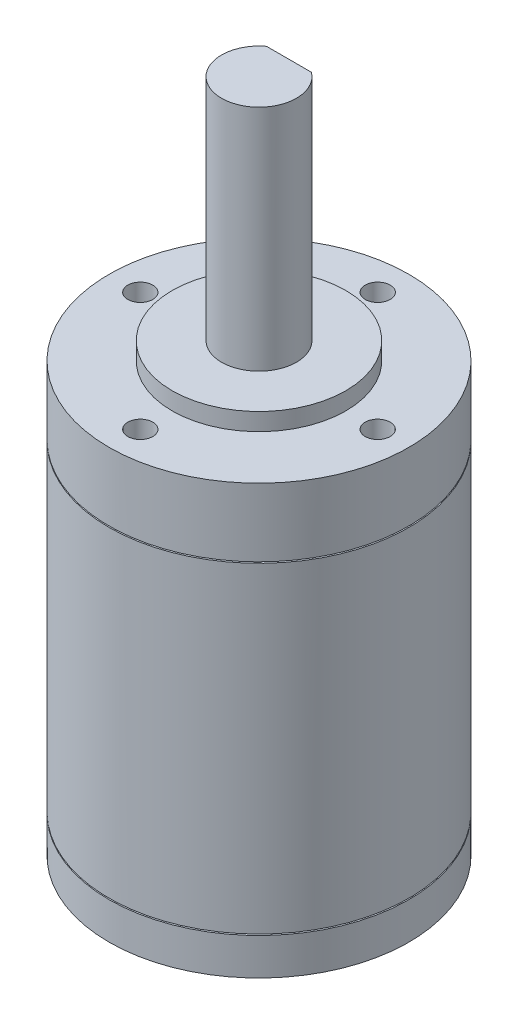
SolidWorks part; units mm, degrees
material "可锻铸铁"
ref_plane "前视" through (0, 0, 0) normal (0, 0, 1) x (1, 0, 0)
ref_plane "上视" through (0, 0, 0) normal (0, 1, 0) x (1, 0, 0)
ref_plane "右视" through (0, 0, 0) normal (1, 0, 0) x (0, 0, -1)
sketch "草图1" plane through (0, 0, 0) normal (0, 1, 0) x (1, 0, 0)
  circle A0 centre (0, 0) radius 12
  dimension "D1" = 24
extrude "凸台-拉伸1" add sketch "草图1" along normal blind 34.3
shell "抽壳6" thickness 2.1
sketch "草图2" plane through (0, 34.3, 0) normal (0, 1, 0) x (1, 0, 0)
  circle A0 centre (0, 0) radius 6.95
  dimension "D1" = 13.9
extrude "凸台-拉伸2" add sketch "草图2" along normal blind 1.4
sketch "草图3" plane through (0, 35.7, 0) normal (0, 1, 0) x (1, 0, 0)
  circle A0 centre (0, 0) radius 3
  dimension "D1" = 6
extrude "凸台-拉伸3" add sketch "草图3" along normal blind 18.3
sketch "草图4" plane through (0, 54, 0) normal (0, 1, 0) x (1, 0, 0)
  line L0 (-4.1804, 2.4) -> (5.155, 2.4)
  line L1 (5.155, 2.4) -> (-0.7181, 5.6828)
  line L2 (-0.7181, 5.6828) -> (-4.1804, 2.4)
  dimension "D1" = 2.4
extrude "切除-拉伸1" cut sketch "草图4" against normal blind 15
sketch "草图5" plane through (0, 0, 0) normal (0, -1, 0) x (1, 0, 0)
  circle A0 centre (0, 0) radius 3.1
  dimension "D1" = 6.2
extrude "切除-拉伸2" cut sketch "草图5" against normal blind 10
chamfer "倒角1" distance 0.9 angle 45 1 edges at (0, 0, -3.1)
sketch "草图7" plane through (0, 34.3, 0) normal (0, 1, 0) x (1, 0, 0)
  circle A0 centre (0, 9.5) radius 1
  dimension "D1" = 2
  dimension "D2" = 9.5
extrude "切除-拉伸3" cut sketch "草图7" against normal blind 10
pattern_circular "阵列(圆周)1" count 4 over 360 about axis through (0, 0, 0) along (0, 1, 0) of "切除-拉伸3"
sketch "草图8" plane through (0, 0, 0) normal (0, -1, 0) x (1, 0, 0)
  circle A0 centre (0, 8) radius 1.5
  dimension "D1" = 3
  dimension "D2" = 8
extrude "切除-拉伸4" cut sketch "草图8" against normal blind 10
pattern_circular "阵列(圆周)2" count 2 over 360 about axis through (0, 0, 0) along (0, 1, 0) of "切除-拉伸4"
sketch "草图10" plane through (0, 0, 0) normal (0, 0, 1) x (1, 0, 0)
  line L0 (-45.6772, 28.8) -> (29.4357, 28.8) construction
  line L1 (-39.0254, 3) -> (32.9484, 3) construction
  line L2 (10.5, 34.3) -> (8.5, 34.3) construction
  line L3 (-12, 0) -> (12, 0) construction
  line L4 (12, 0) -> (12, 34.3) construction
  line L5 (11.3902, 28.75) -> (12.3902, 28.75)
  line L6 (11.3902, 28.75) -> (11.3902, 28.85)
  line L7 (11.3902, 28.85) -> (12.3902, 28.85)
  line L8 (12.3902, 28.75) -> (12.3902, 28.85)
  line L9 (11.3902, 28.75) -> (12.3902, 28.85) construction
  line L10 (11.3902, 28.85) -> (12.3902, 28.75) construction
  line L11 (11.5, 2.95) -> (12.5, 2.95)
  line L12 (11.5, 2.95) -> (11.5, 3.05)
  line L13 (11.5, 3.05) -> (12.5, 3.05)
  line L14 (12.5, 2.95) -> (12.5, 3.05)
  line L15 (11.5, 2.95) -> (12.5, 3.05) construction
  line L16 (11.5, 3.05) -> (12.5, 2.95) construction
  line L17 (0, 62.1821) -> (0, -15.2994) construction
  point P8 (11.8902, 28.8)
  point P13 (12, 3)
  dimension "D1" = 5.5
  dimension "D2" = 3
  dimension "D3" = 1
  dimension "D4" = 1
  dimension "D5" = 0.1
  dimension "D6" = 0.1
revolve "切除-旋转1" cut sketch "草图10" angle 360 about L17
